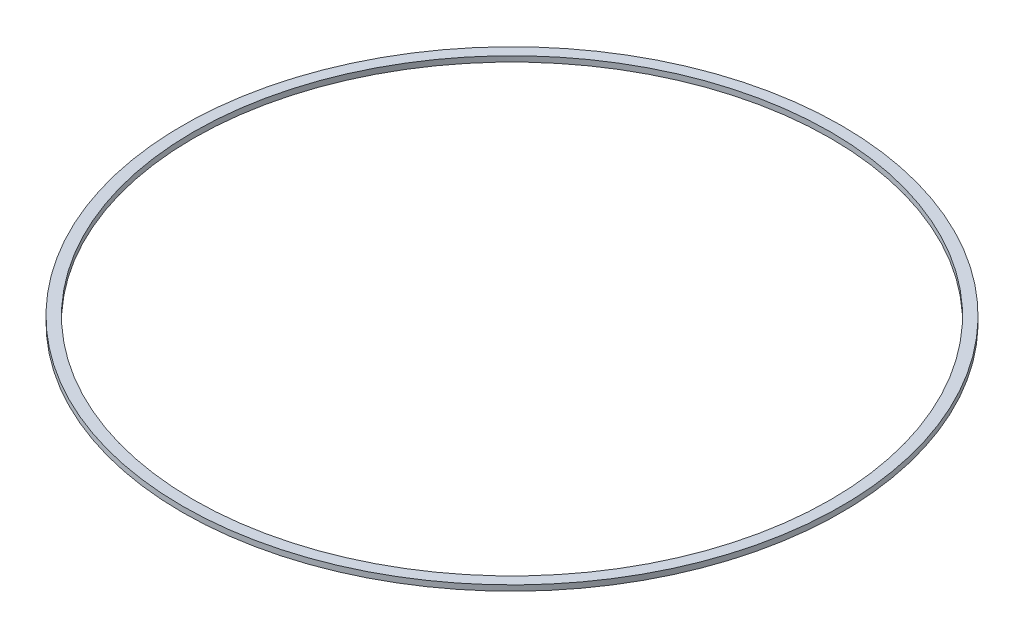
SolidWorks part; units mm, degrees
ref_plane "Front" through (0, 0, 0) normal (0, 0, 1) x (1, 0, 0)
ref_plane "Top" through (0, 0, 0) normal (0, 1, 0) x (1, 0, 0)
ref_plane "Right" through (0, 0, 0) normal (1, 0, 0) x (0, 0, -1)
sketch "Sketch1" plane through (0, 0, 0) normal (0, 0, 1) x (1, 0, 0)
  line L0 (-11.5057, 2.2657) -> (-11.5057, -1.6363) construction
  line L1 (17.4943, 0.8571) -> (18.4943, 0.8571)
  line L2 (17.4943, 0.8571) -> (17.4943, 0.3571)
  line L3 (17.4943, 0.3571) -> (18.4943, 0.3571)
  line L4 (18.4943, 0.8571) -> (18.4943, 0.3571)
  point P6 (0, 0)
  dimension "D1" = 1
  dimension "D2" = 0.5
  dimension "D3" = 3.902
  dimension "D4" = 30
revolve "Revolve1" add sketch "Sketch1" angle 360 about L0
